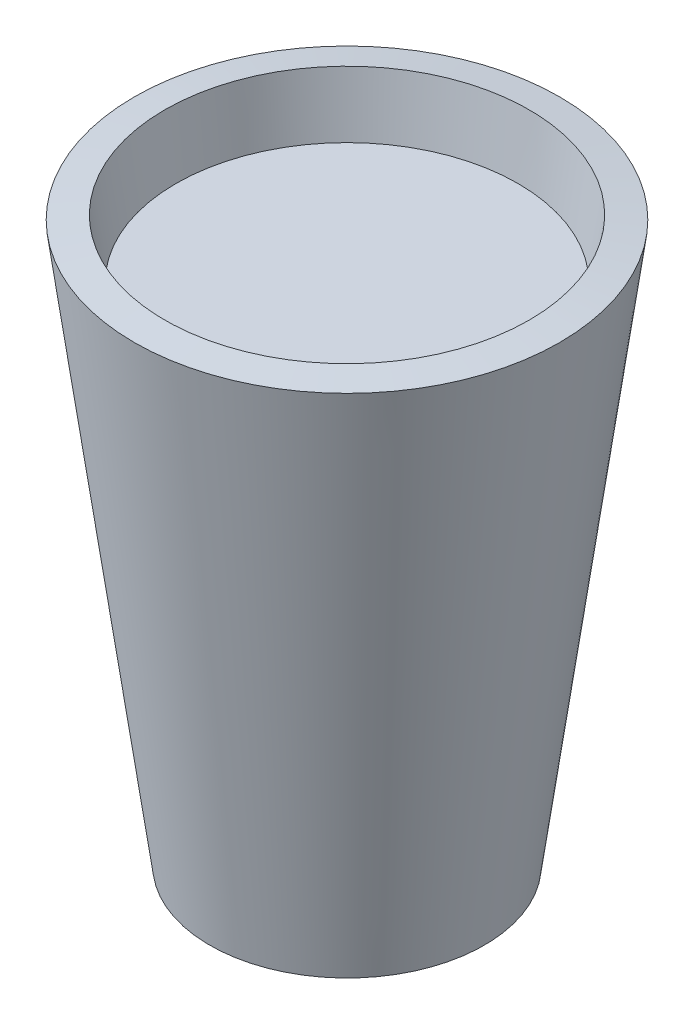
SolidWorks part; units mm, degrees
ref_plane "Front Plane" through (0, 0, 0) normal (0, 0, 1) x (1, 0, 0)
ref_plane "Top Plane" through (0, 0, 0) normal (0, 1, 0) x (1, 0, 0)
ref_plane "Right Plane" through (0, 0, 0) normal (1, 0, 0) x (0, 0, -1)
sketch "Sketch1" plane through (0, 0, 0) normal (0, 0, 1) x (1, 0, 0)
  line L0 (0, 0) -> (28.575, 0)
  line L4 (22.225, 10.16) -> (0, 10.16)
  line L5 (0, 10.16) -> (0, 0)
  line L6 (28.575, 0) -> (44.2525, 116.4242)
  line L7 (44.2525, 116.4242) -> (37.9025, 117.2793)
  line L8 (37.9025, 117.2793) -> (22.225, 10.16)
  dimension "D1" = 28.575
  dimension "D2" = 6.35
  dimension "D3" = 117.475
  dimension "D4" = 10.16
revolve "Revolve4" add sketch "Sketch1" angle 360 about L5
sketch "Sketch2" plane through (0, 10.16, 0) normal (0, 1, 0) x (1, 0, 0)
  circle A0 centre (0, 0) radius 22.225
extrude "Boss-Extrude1" add sketch "Sketch2" along normal blind 94.996 draft 8 draft outward yes
